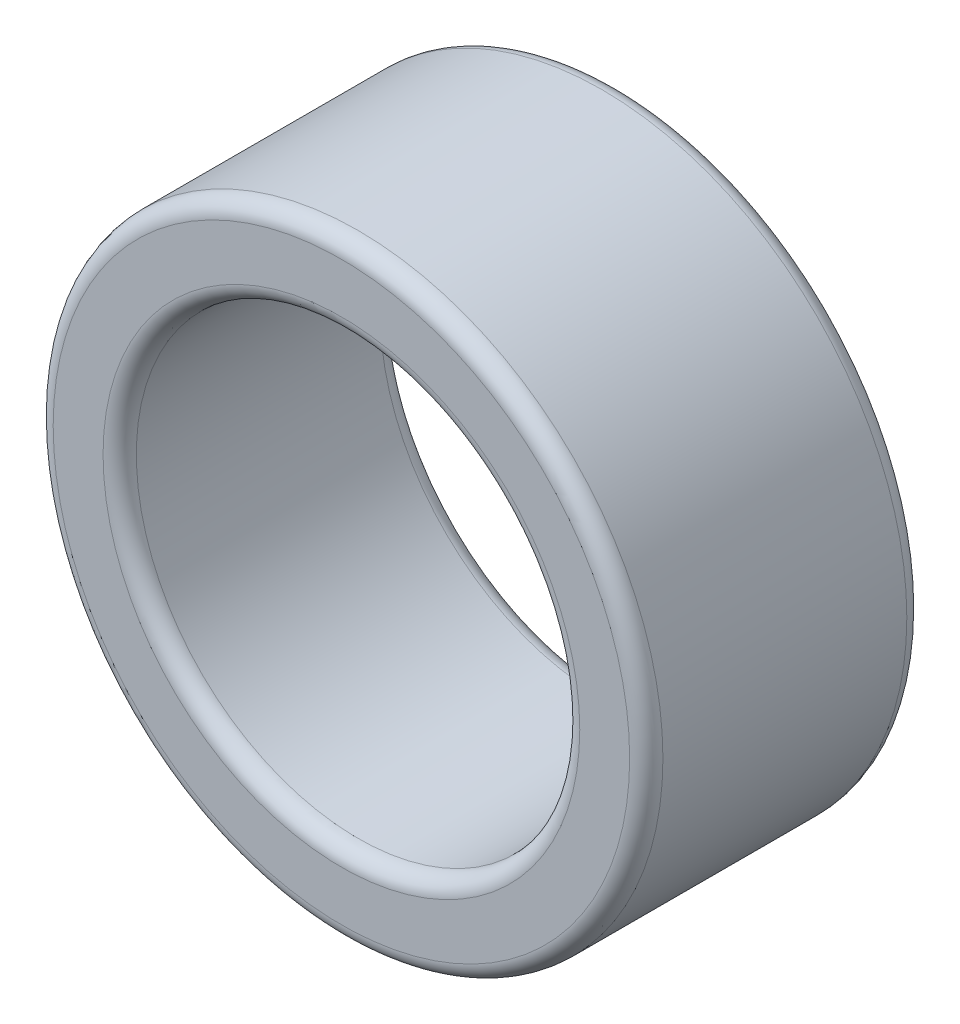
SolidWorks part; units mm, degrees
ref_plane "Front Plane" through (0, 0, 0) normal (0, 0, 1) x (1, 0, 0)
ref_plane "Top Plane" through (0, 0, 0) normal (0, 1, 0) x (1, 0, 0)
ref_plane "Right Plane" through (0, 0, 0) normal (1, 0, 0) x (0, 0, -1)
sketch "Sketch1" plane through (0, 0, 0) normal (0, 0, 1) x (1, 0, 0)
  circle A0 centre (0, 0) radius 4
  circle A1 centre (0, 0) radius 5.5
  dimension "D1" = 8
  dimension "D2" = 11
extrude "Boss-Extrude1" add sketch "Sketch1" along normal blind 5
fillet "Fillet1" radius 0.3 1 edges at (5.5, 0, 0)
fillet "Fillet2" radius 0.3 1 edges at (4, 0, 0)
fillet "Fillet3" radius 0.3 2 edges at (4, 0, 5) (5.5, 0, 5)
